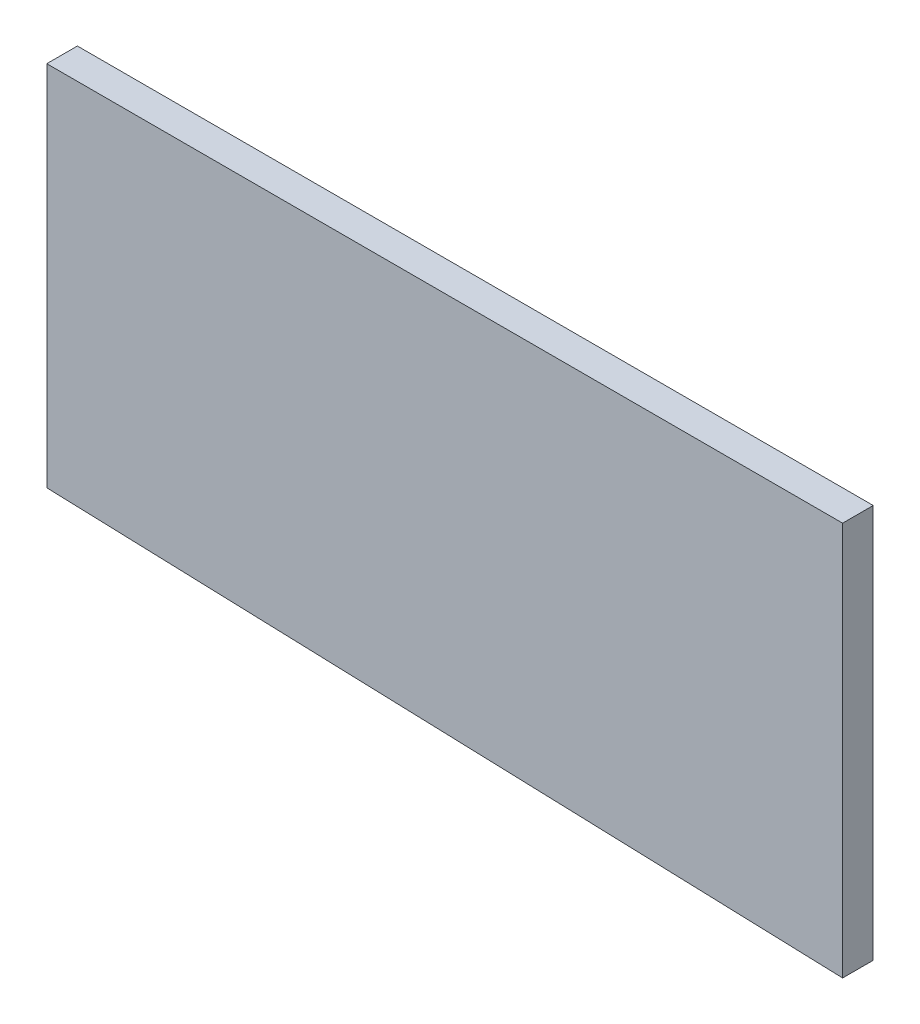
SolidWorks part; units mm, degrees
ref_plane "Front Plane" through (0, 0, 0) normal (0, 0, 1) x (1, 0, 0)
ref_plane "Top Plane" through (0, 0, 0) normal (0, 1, 0) x (1, 0, 0)
ref_plane "Right Plane" through (0, 0, 0) normal (1, 0, 0) x (0, 0, -1)
sketch "Sketch1" plane through (0, 0, 0) normal (0, 0, 1) x (1, 0, 0)
  line L0 (0, 0) -> (130, 0)
  line L1 (130, 0) -> (130, -64.3464)
  line L2 (130, -64.3464) -> (0, -60)
  line L3 (0, -60) -> (0, 0)
  dimension "D1" = 130
  dimension "D2" = 60
extrude "Boss-Extrude1" add sketch "Sketch1" along normal blind 5
